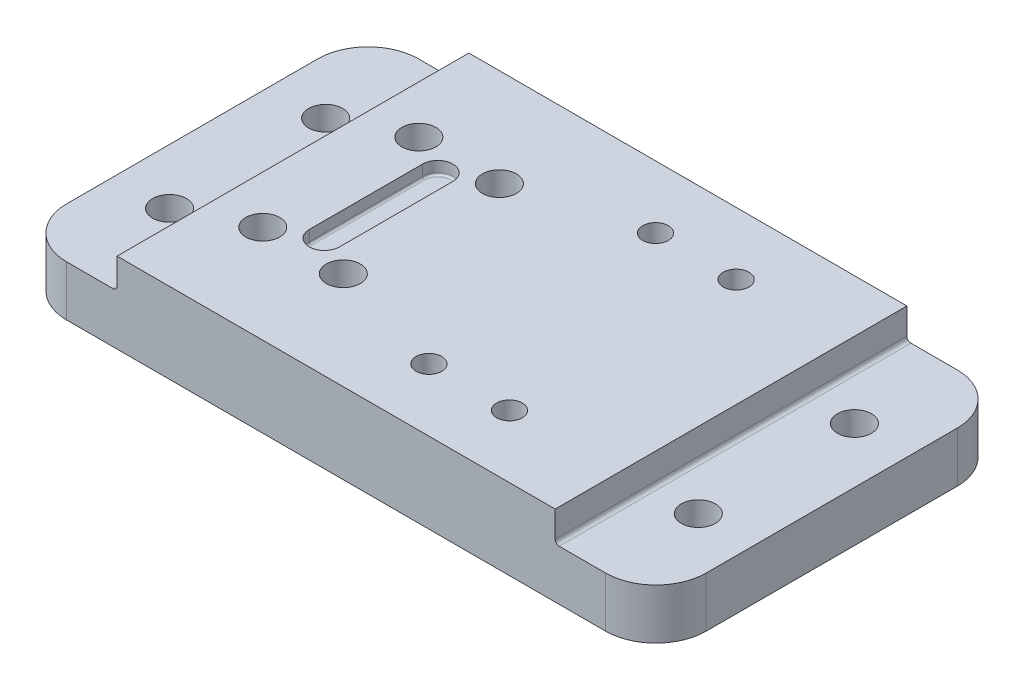
SolidWorks part; units mm, degrees
material "Low Carbon Steel"
ref_plane "Front Plane" through (0, 0, 0) normal (0, 0, 1) x (1, 0, 0)
ref_plane "Top Plane" through (0, 0, 0) normal (0, 1, 0) x (1, 0, 0)
ref_plane "Right Plane" through (0, 0, 0) normal (1, 0, 0) x (0, 0, -1)
sketch "Sketch1" plane through (0, 0, 0) normal (0, 1, 0) x (1, 0, 0)
  line L0 (-127, -69.85) -> (127, 69.85) construction
  line L1 (-127, 69.85) -> (127, 69.85)
  line L2 (-127, 69.85) -> (-127, -69.85)
  line L3 (-127, -69.85) -> (127, -69.85)
  line L4 (127, 69.85) -> (127, -69.85)
  dimension "D1" = 139.7
  dimension "D2" = 254
extrude "Boss-Extrude1" add sketch "Sketch1" along normal mid plane 38.1
fillet "Fillet1" radius 20 4 edges at (127, 0, -69.85) (-127, 0, -69.85) (-127, 0, 69.85) (127, 0, 69.85)
sketch "Sketch2" plane through (0, 0, 69.85) normal (0, 0, 1) x (1, 0, 0)
  line L0 (127, 19.05) -> (127, -19.05) construction
  line L1 (-127, 19.05) -> (127, 19.05)
  line L2 (-127, 19.05) -> (-127, 16)
  line L3 (-127, 16) -> (127, 16)
  line L4 (127, 19.05) -> (127, 16)
  line L5 (-127, -19.05) -> (-127, 19.05) construction
  line L6 (127, -19.05) -> (-127, -19.05)
  line L7 (127, -19.05) -> (127, -16)
  line L8 (127, -16) -> (-127, -16)
  line L9 (-127, -19.05) -> (-127, -16)
  dimension "D1" = 32
extrude "Cut-Extrude1" cut sketch "Sketch2" against normal through all
sketch "Sketch8" plane through (0, 16, 0) normal (0, 1, 0) x (1, 0, 0)
  line L0 (-107, 69.85) -> (107, 69.85) construction
  line L1 (-87, 69.85) -> (-127, 69.85)
  line L2 (-87, 69.85) -> (-87, -69.85)
  line L3 (-87, -69.85) -> (-127, -69.85)
  line L4 (-127, 69.85) -> (-127, -69.85)
  line L5 (-107, -69.85) -> (107, -69.85) construction
  line L6 (127, 49.85) -> (127, -49.85) construction
  line L7 (87, -69.85) -> (127, -69.85)
  line L8 (87, -69.85) -> (87, 69.85)
  line L9 (87, 69.85) -> (127, 69.85)
  line L10 (127, -69.85) -> (127, 69.85)
  line L11 (-127, 49.85) -> (-127, -49.85) construction
  dimension "D1" = 40
  dimension "D2" = 40
extrude "Cut-Extrude2" cut sketch "Sketch8" against normal blind 12
hole_wizard "M12 Tapped Hole2" positions "Sketch4" profile "Sketch3" tap size "M12" standard "Peddi DIN"
sketch "Sketch4" plane through (0, 16, 0) normal (0, -1, 0) x (-1, 0, 0)
  line L0 (-12, 45) -> (-44, 45) construction
  line L1 (-44, 45) -> (-44, -45) construction
  line L3 (-44, -45) -> (-12, -45) construction
  line L4 (-12, -45) -> (-12, 45) construction
  line L11 (0, 0) -> (-12, 0) construction
  line L15 (-127, 49.85) -> (-127, -49.85) construction
  point P8 (-12, -45)
  point P10 (-12, 45)
  point P12 (-44, 45)
  point P14 (-44, -45)
  dimension "D1" = 90
  dimension "D2" = 32
  dimension "D6" = 83
sketch "Sketch3" plane through (12, 16, 45) normal (1, 0, 0) x (0, 0, 1)
  line L0 (0, 0) -> (0, 47.0544)
  line L1 (0, 47.0544) -> (5.1, 43.99)
  line L2 (5.1, 43.99) -> (5.1, 0)
  line L5 (5.1, 0) -> (0, 0)
  line L10 (0, 47.0544) -> (-5.1, 43.99) construction
  line L11 (0, -6.35) -> (0, 107.95) construction
  dimension "Tap Drill Dia." = 10.2
  dimension "Tap Drill Depth" = 43.99
  dimension "Drill Angle" = 118
cosmetic thread "Hole Thread13" parameters "D1"=30, "D2"=12
cosmetic thread "Hole Thread14" parameters "D1"=30, "D2"=12
cosmetic thread "Hole Thread15" parameters "D1"=30, "D2"=12
cosmetic thread "Hole Thread16" parameters "D1"=30, "D2"=12
hole_wizard "M12 Clearance Hole1" positions "Sketch6" profile "Sketch7" hole size "M12" standard "Peddi DIN" end condition through all
sketch "Sketch6" plane through (0, 4, 0) normal (0, 1, 0) x (1, 0, 0)
  line L0 (-105, 31) -> (-105, -31) construction
  line L2 (-105, 0) -> (0, 0) construction
  line L5 (-105, 31) -> (105, 31) construction
  line L6 (105, 31) -> (105, -31) construction
  line L7 (105, -31) -> (-105, -31) construction
  point P0 (-105, 31)
  point P2 (-105, -31)
  point P20 (105, 31)
  point P22 (105, -31)
  dimension "D1" = 105
  dimension "D2" = 210
  dimension "D3" = 62
sketch "Sketch7" plane through (-105, 4, -31) normal (1, 0, 0) x (0, 0, 1)
  line L0 (0, 0) -> (0, 20)
  line L1 (0, 20) -> (6.75, 20)
  line L2 (6.75, 20) -> (6.75, 0)
  line L5 (6.75, 0) -> (0, 0)
  line L11 (0, -6.35) -> (0, 107.95) construction
  dimension "Thru Hole Dia." = 13.5
  dimension "Thru Hole Depth" = 20
hole_wizard "CBORE for M12 Hex Socket Head Cap Screw1" positions "Sketch9" profile "Sketch10" counterbore size "M12" standard "Peddi DIN" end condition through all
sketch "Sketch9" plane through (0, -16, 0) normal (0, 1, 0) x (1, 0, 0)
  line L1 (-36, 31) -> (-68, 31) construction
  line L2 (-36, 31) -> (-36, -31) construction
  line L3 (-36, -31) -> (-68, -31) construction
  line L4 (-68, 31) -> (-68, -31) construction
  line L5 (0, 0) -> (-36, 0) construction
  circle A1 centre (12, -45) radius 5.1 construction
  point P0 (-36, 31)
  point P1 (-68, -31)
  point P28 (-36, -31)
  point P29 (-68, 31)
  dimension "D1" = 62
  dimension "D2" = 32
  dimension "D3" = 48
sketch "Sketch10" plane through (-36, -16, -31) normal (1, 0, 0) x (0, 0, -1)
  line L0 (0, 0) -> (0, 32)
  line L1 (0, 32) -> (6.75, 32)
  line L3 (6.75, 32) -> (6.75, 13)
  line L4 (6.75, 13) -> (10, 13)
  line L5 (10, 13) -> (10, 0)
  line L7 (10, 0) -> (0, 0)
  line L11 (0, -6.35) -> (0, 107.95) construction
  dimension "Thru Hole Dia." = 13.5
  dimension "Thru Hole Depth" = 32
  dimension "C'Bore Dia." = 20
  dimension "C'Bore Depth" = 13
sketch "Sketch11" plane through (0, 16, 0) normal (0, 1, 0) x (1, 0, 0)
  line L0 (-52, 22.5) -> (-52, -22.5) construction
  line L1 (-46, 22.5) -> (-46, -22.5)
  line L2 (-58, 22.5) -> (-58, -22.5)
  line L3 (-68, 31) -> (-36, -31) construction
  arc A0 (-46, 22.5) -> (-58, 22.5) centre (-52, 22.5) ccw
  arc A1 (-58, -22.5) -> (-46, -22.5) centre (-52, -22.5) ccw
  point P2 (-52, 0)
  dimension "D1" = 12
  dimension "D2" = 45
extrude "Cut-Extrude3" cut sketch "Sketch11" against normal blind 5.08
fillet "Fillet2" radius 0.7937 4 edges at (-52, 10.92, -28.5) (-46, 10.92, 0) (-52, 10.92, 28.5) (-58, 10.92, 0)
fillet "Fillet3" radius 1.5875 2 edges at (-87, 4, 0) (87, 4, 0)
other "Freeze***"
